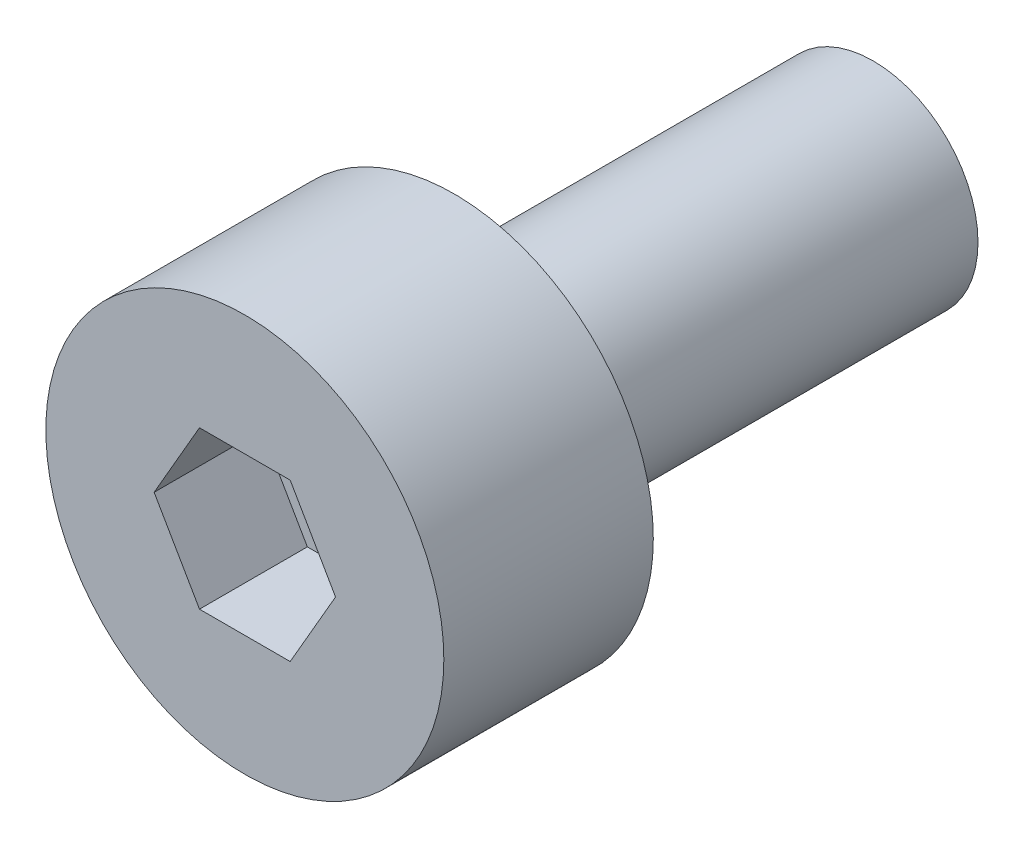
SolidWorks part; units mm, degrees
ref_plane "前视基准面" through (0, 0, 0) normal (0, 0, 1) x (1, 0, 0)
ref_plane "上视基准面" through (0, 0, 0) normal (0, 1, 0) x (1, 0, 0)
ref_plane "右视基准面" through (0, 0, 0) normal (1, 0, 0) x (0, 0, -1)
other "Configuration Table"
sketch "ISO4762_head_Sketch" plane through (0, 0, 0) normal (0, 0, 1) x (1, 0, 0)
  circle A0 centre (0, 0) radius 1.9
extrude "ISO4762_head" add sketch "ISO4762_head_Sketch" along normal blind 2 separate body
sketch "Thread_major_diameter_envelope_Sketch" plane through (0, 0, 0) normal (0, 0, 1) x (1, 0, 0)
  circle A0 centre (0, 0) radius 1
extrude "Thread_major_diameter_envelope" add sketch "Thread_major_diameter_envelope_Sketch" along normal blind 4 from offset 4
sketch "Hex_socket_Sketch" plane through (0, 0, 0) normal (0, 0, 1) x (1, 0, 0)
  line L0 (0.866, 0) -> (0.433, 0.75)
  line L1 (0.433, 0.75) -> (-0.433, 0.75)
  line L2 (-0.433, 0.75) -> (-0.866, 0)
  line L3 (-0.866, 0) -> (-0.433, -0.75)
  line L4 (-0.433, -0.75) -> (0.433, -0.75)
  line L5 (0.433, -0.75) -> (0.866, 0)
extrude "Hex_socket" cut sketch "Hex_socket_Sketch" along normal blind 1.03 from offset 0.97
